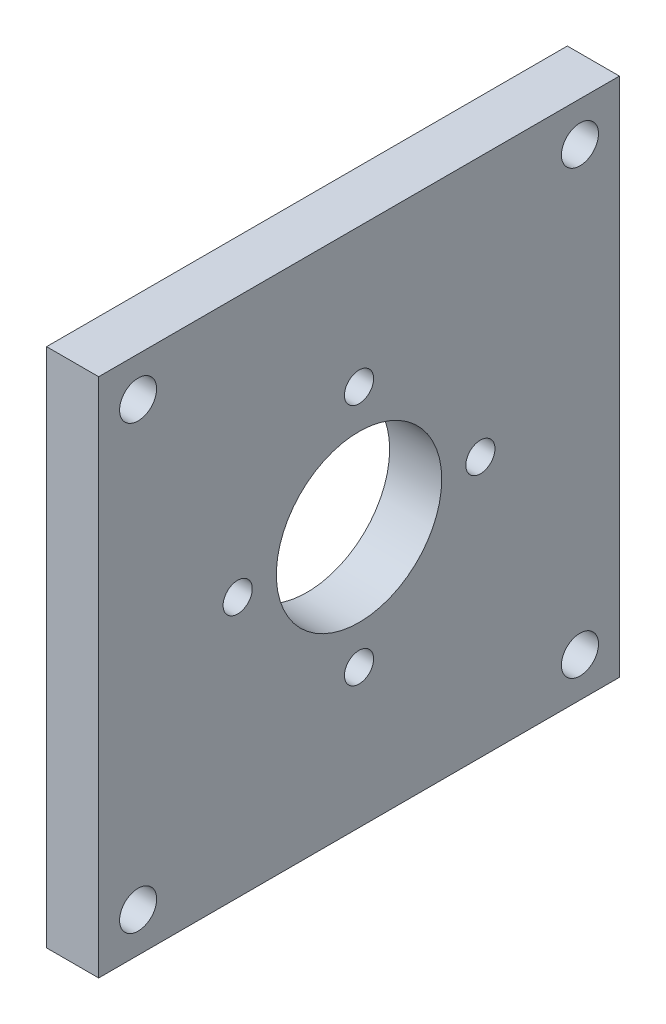
SolidWorks part; units mm, degrees
material "Nylon 6/10"
ref_plane "Front Plane" through (0, 0, 0) normal (0, 0, 1) x (1, 0, 0)
ref_plane "Top Plane" through (0, 0, 0) normal (0, 1, 0) x (1, 0, 0)
ref_plane "Right Plane" through (0, 0, 0) normal (1, 0, 0) x (0, 0, -1)
sketch "Sketch1" plane through (0, 0, 0) normal (1, 0, 0) x (0, 0, -1)
  line L1 (-15.875, -15.875) -> (15.875, -15.875)
  line L2 (-15.875, -15.875) -> (-15.875, 15.875)
  line L3 (-15.875, 15.875) -> (15.875, 15.875)
  line L4 (15.875, -15.875) -> (15.875, 15.875)
  line L5 (-15.875, -15.875) -> (15.875, 15.875) construction
  line L6 (-15.875, 15.875) -> (15.875, -15.875) construction
  point P0 (0, 0)
  dimension "D1" = 31.75
  dimension "D2" = 31.75
extrude "Boss-Extrude1" add sketch "Sketch1" along normal blind 3.175
hole_wizard "X (0.397) Diameter Hole1" positions "Sketch3" profile "Sketch2" hole size "X" standard "ANSI Inch"
sketch "Sketch3" plane through (3.175, 0, 0) normal (1, 0, 0) x (0, 0, -1)
  point P0 (0, 0)
sketch "Sketch2" plane through (3.175, 0, 0) normal (0, 1, 0) x (0, 0, -1)
  line L0 (0, 0) -> (0, 15.7295)
  line L1 (0, 15.7295) -> (5.0419, 12.7)
  line L2 (5.0419, 12.7) -> (5.0419, 0)
  line L5 (5.0419, 0) -> (0, 0)
  line L10 (0, 15.7295) -> (-5.0419, 12.7) construction
  line L11 (0, -6.35) -> (0, 107.95) construction
  dimension "Hole Dia." = 10.0838
  dimension "Hole Depth" = 12.7
  dimension "Drill Angle" = 118
hole_wizard "#2-56 Tapped Hole1" positions "Sketch5" profile "Sketch4" tap size "#2-56" standard "ANSI Inch"
sketch "Sketch5" plane through (3.175, 0, 0) normal (1, 0, 0) x (0, 0, -1)
  point P0 (0, 7.4)
  dimension "D1" = 7.4
sketch "Sketch4" plane through (3.175, 7.4, 0) normal (0, 1, 0) x (0, 0, -1)
  line L0 (0, 0) -> (0, 7.1382)
  line L1 (0, 7.1382) -> (0.889, 6.604)
  line L2 (0.889, 6.604) -> (0.889, 0)
  line L5 (0.889, 0) -> (0, 0)
  line L10 (0, 7.1382) -> (-0.889, 6.604) construction
  line L11 (0, -6.35) -> (0, 107.95) construction
  dimension "Tap Drill Dia." = 1.778
  dimension "Tap Drill Depth" = 6.604
  dimension "Drill Angle" = 118
pattern_circular "CirPattern1" count 4 over 360 about axis through (0, 0, 0) along (1, 0, 0) of "#2-56 Tapped Hole1"
hole_wizard "#4-40 Tapped Hole1" positions "Sketch7" profile "Sketch6" tap size "#4-40" standard "ANSI Inch"
sketch "Sketch7" plane through (3.175, 0, 0) normal (1, 0, 0) x (0, 0, -1)
  line L0 (0, -15.875) -> (0, 15.875) construction
  line L1 (-15.875, -15.875) -> (15.875, -15.875) construction
  line L2 (15.875, 15.875) -> (-15.875, 15.875) construction
  line L3 (0, 0) -> (-13.4704, 13.4704) construction
  point P0 (-13.4704, 13.4704)
  dimension "D1" = 45
  dimension "D2" = 19.05
sketch "Sketch6" plane through (3.175, 13.4704, 13.4704) normal (0, 1, 0) x (0, 0, -1)
  line L0 (0, 0) -> (0, 9.5692)
  line L1 (0, 9.5692) -> (1.1303, 8.89)
  line L2 (1.1303, 8.89) -> (1.1303, 0)
  line L5 (1.1303, 0) -> (0, 0)
  line L10 (0, 9.5692) -> (-1.1303, 8.89) construction
  line L11 (0, -6.35) -> (0, 107.95) construction
  dimension "Tap Drill Dia." = 2.2606
  dimension "Tap Drill Depth" = 8.89
  dimension "Drill Angle" = 118
pattern_circular "CirPattern2" count 4 over 360 about axis through (0, 0, 0) along (1, 0, 0) of "#4-40 Tapped Hole1"
